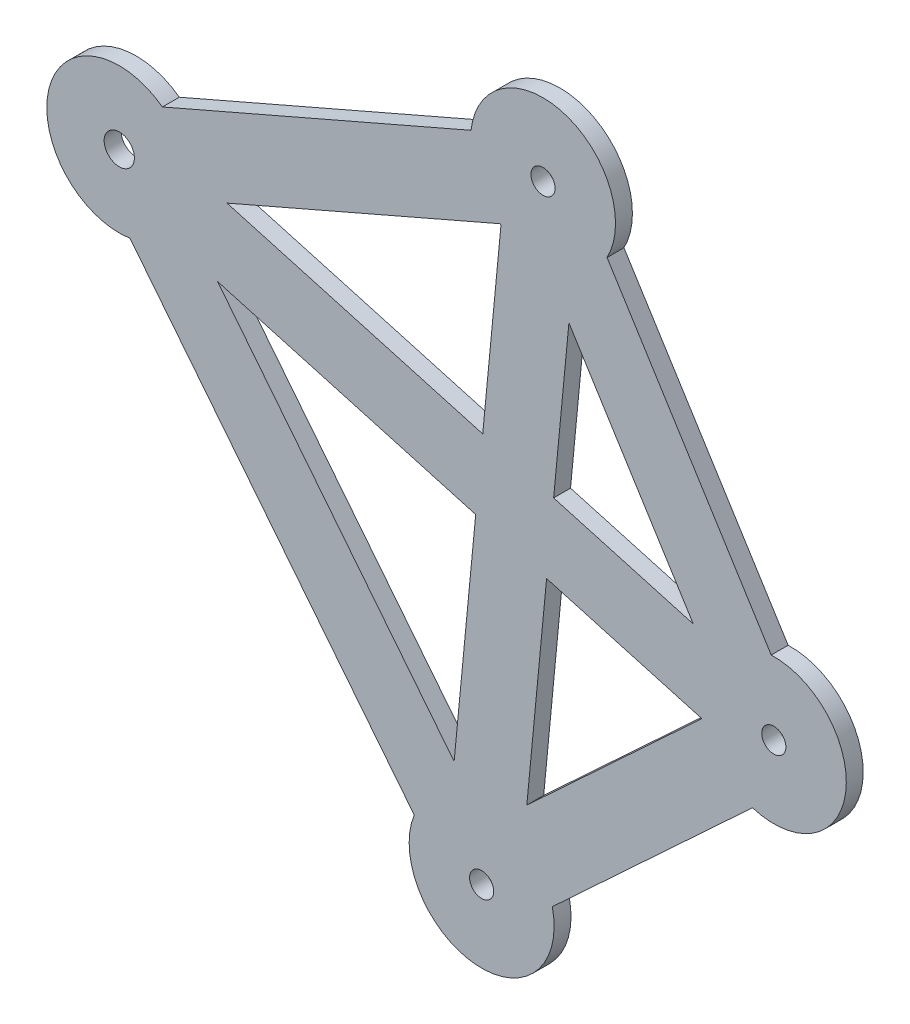
SolidWorks part; units mm, degrees
material "Cedar"
ref_plane "Front Plane" through (0, 0, 0) normal (0, 0, 1) x (1, 0, 0)
ref_plane "Top Plane" through (0, 0, 0) normal (0, 1, 0) x (1, 0, 0)
ref_plane "Right Plane" through (0, 0, 0) normal (1, 0, 0) x (0, 0, -1)
sketch "Sketch2" plane through (0, 0, 0) normal (0, 0, 1) x (1, 0, 0)
  line L1 (228.6, -228.6) -> (-228.6, -228.6)
  line L2 (228.6, -228.6) -> (228.6, 228.6)
  line L3 (228.6, 228.6) -> (-228.6, 228.6)
  line L4 (-228.6, -228.6) -> (-228.6, 228.6)
  line L5 (228.6, -228.6) -> (-228.6, 228.6) construction
  line L6 (228.6, 228.6) -> (-228.6, -228.6) construction
  point P0 (0, 0)
  dimension "D1" = 457.2
  dimension "D2" = 457.2
extrude "Boss-Extrude3" add sketch "Sketch2" along normal blind 4.445
sketch "Sketch3" plane through (0, 0, 0) normal (0, 0, -1) x (-1, 0, 0)
  circle A0 centre (-138.1432, 71.8714) radius 3.175
  circle A1 centre (-198.8095, -25.0001) radius 3.175
  circle A2 centre (-122.0047, -96.2659) radius 3.175
  circle A3 centre (-26.7547, -96.2659) radius 3.175
  circle A4 centre (-26.7547, 23.4697) radius 3.9751
  dimension "D1" = 6.35
  dimension "D2" = 6.35
  dimension "D3" = 6.35
  dimension "D4" = 6.35
  dimension "D5" = 7.9502
extrude "Cut-Extrude1" cut sketch "Sketch3" against normal through all
sketch "Sketch4" plane through (0, 0, 4.445) normal (0, 0, 1) x (1, 0, 0)
  line L0 (29.5712, 4.6291) -> (104.2799, -89.2848)
  line L1 (44.4794, 16.4886) -> (119.1881, -77.4253)
  line L2 (180.2372, -29.2393) -> (127.6196, -78.0622)
  line L3 (193.1946, -43.2038) -> (140.577, -92.0267)
  line L4 (154.9723, 62.9447) -> (198.1257, -5.9624)
  line L5 (138.827, 52.8336) -> (181.9805, -16.0735)
  line L6 (11.8465, 11.6102) -> (107.0965, -108.1254) construction
  line L7 (157.106, 70.0512) -> (140.9675, -98.086) construction
  line L8 (38.0897, 38.7805) -> (119.2162, 74.0324)
  line L9 (45.6817, 21.3087) -> (126.8082, 56.5606)
  line L10 (19.1626, 40.9415) -> (130.5512, 89.3432) construction
  line L11 (154.2884, 81.9824) -> (214.9548, -14.8891) construction
  line L12 (211.767, -38.9646) -> (134.9621, -110.2304) construction
  line L13 (127.0855, 56.3591) -> (114.0995, -78.9335)
  line L14 (146.0483, 54.539) -> (133.0624, -80.7536)
  line L16 (31.9202, 41.806) -> (203.9751, -6.6638) construction
  line L17 (45.2171, 28.1644) -> (185.5126, -11.3585)
  line L18 (40.0516, 9.8281) -> (180.3471, -29.6948)
  line L22 (-228.6, 228.6) -> (228.6, 228.6)
  line L23 (-228.6, 228.6) -> (-228.6, -228.8013)
  line L24 (228.6, 228.6) -> (228.6, -228.8013)
  line L25 (-228.6, -228.8013) -> (228.6, -228.8013)
  circle A0 centre (26.7547, 23.4697) radius 19.05
  circle A1 centre (138.1432, 71.8714) radius 19.05
  circle A2 centre (198.8095, -25.0001) radius 19.05
  circle A3 centre (122.0047, -96.2659) radius 19.05
  point P55 (97.706, -6.4138)
  circle M2 centre (26.7547, -96.2659) radius 3.175
  line M6 (-228.6, 228.6) -> (-228.6, -228.6)
  line M7 (-228.6, -228.6) -> (228.6, -228.6)
  line M8 (228.6, -228.6) -> (228.6, 228.6)
  line M9 (228.6, 228.6) -> (-228.6, 228.6)
  dimension "D1" = 38.1
  dimension "D2" = 19.05
  dimension "D3" = 19.05
  dimension "D4" = 19.05
  dimension "D5" = 19.05
  dimension "D6" = 19.05
  dimension "D8" = 19.05
extrude "Cut-Extrude2" cut sketch "Sketch4" against normal through all contours A3 L0 A0 L8 A1 L4 A2 L3 M9 M6 M7 M8 M2 | A1 L9 L17 L13 | L14 L17 L5 | L18 L14 L2 | L18 L1 L13
